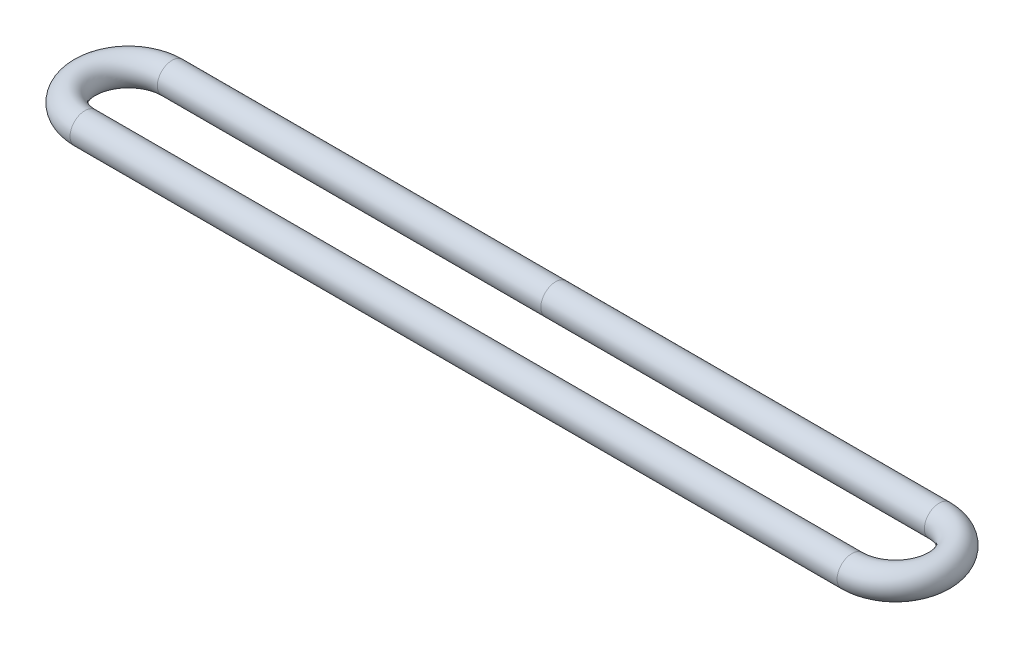
SolidWorks part; units mm, degrees
material "Plain Carbon Steel"
ref_plane "Front Plane" through (0, 0, 0) normal (0, 0, 1) x (1, 0, 0)
ref_plane "Top Plane" through (0, 0, 0) normal (0, 1, 0) x (1, 0, 0)
ref_plane "Right Plane" through (0, 0, 0) normal (1, 0, 0) x (0, 0, -1)
sketch "Sketch7" plane through (0, 0, 0) normal (0, 1, 0) x (1, 0, 0)
  line L0 (-61.7222, -9.2815) -> (61.7222, -9.2815)
  line L1 (61.7222, 0) -> (-61.7222, 0)
  arc A0 (61.7222, -9.2815) -> (61.7222, 0) centre (61.7222, -4.6407) ccw
  arc A1 (-61.7222, 0) -> (-61.7222, -9.2815) centre (-61.7222, -4.6407) ccw
  point P10 (0, 0)
  dimension "D2" = 276.0472
  dimension "D1" = 9.2815
sketch "Sketch8" plane through (0, 0, 0) normal (1, 0, 0) x (0, 0, -1)
  circle A0 centre (2.3813, 0) radius 2.3812
  point P0 (0, 0)
  dimension "D1" = 4.7625
sweep "Sweep2" add profiles "Sketch8" path "Sketch7"
ref_plane "Plane1" through (0, 0, 14.044) normal (0, 0, 1) x (1, 0, 0)
sketch "Sketch9" plane through (0, 0, 0) normal (0, 1, 0) x (1, 0, 0)
  arc A0 (61.7222, -14.044) -> (61.7222, 4.7625) centre (61.7222, -4.6407) ccw construction
  point P0 (71.1254, -4.6407)
ref_plane "Plane2" through (71.1254, 0, 0) normal (1, 0, 0) x (0, 0, -1)
sketch "Sketch10" plane through (0, 0, 0) normal (0, 1, 0) x (1, 0, 0)
  line L0 (-61.7222, -4.6407) -> (61.7222, -4.6407) construction
  line L1 (-61.7222, 0) -> (61.7222, 0)
  line L2 (-61.7222, -9.2815) -> (61.7222, -9.2815)
  line L3 (61.7222, -4.6407) -> (71.1254, -4.6407) construction
  arc A0 (-61.7222, 0) -> (-61.7222, -9.2815) centre (-61.7222, -4.6407) ccw
  arc A1 (61.7222, -9.2815) -> (61.7222, 0) centre (61.7222, -4.6407) ccw
  arc A2 (61.7222, -14.044) -> (61.7222, 4.7625) centre (61.7222, -4.6407) ccw construction
  point P2 (0, -4.6407)
  point P7 (61.7222, 0)
